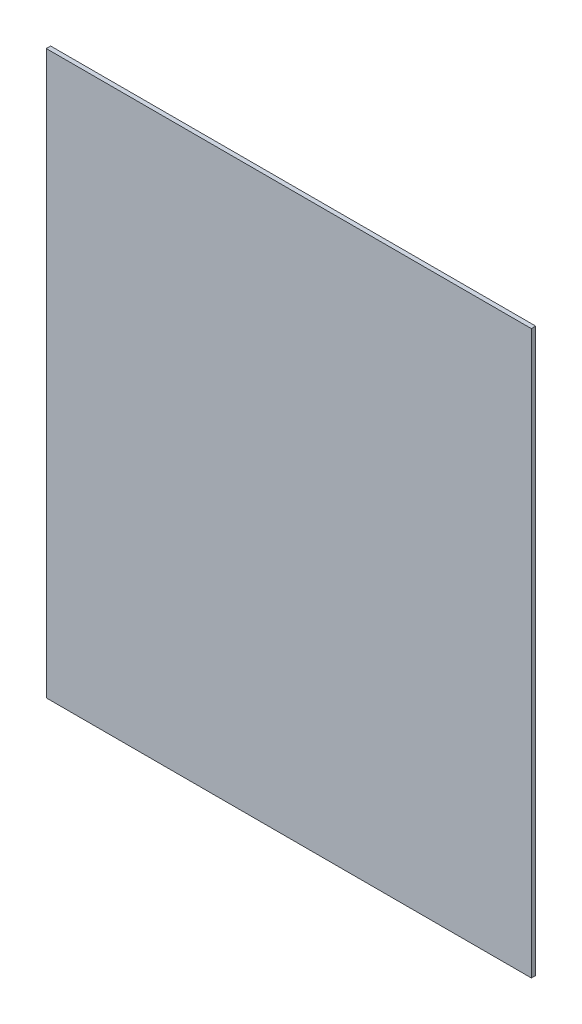
SolidWorks part; units mm, degrees
ref_plane "Plan de face" through (0, 0, 0) normal (0, 0, 1) x (1, 0, 0)
ref_plane "Plan de dessus" through (0, 0, 0) normal (0, 1, 0) x (1, 0, 0)
ref_plane "Plan de droite" through (0, 0, 0) normal (1, 0, 0) x (0, 0, -1)
sketch "Esquisse1" plane through (0, 0, 0) normal (0, 0, 1) x (1, 0, 0)
  line L1 (-361, -418.5) -> (361, -418.5)
  line L2 (-361, -418.5) -> (-361, 418.5)
  line L3 (-361, 418.5) -> (361, 418.5)
  line L4 (361, -418.5) -> (361, 418.5)
  line L5 (-361, -418.5) -> (361, 418.5) construction
  line L6 (-361, 418.5) -> (361, -418.5) construction
  point P0 (0, 0)
  dimension "D1" = 837
  dimension "D2" = 722
extrude "Boss.-Extru.1" add sketch "Esquisse1" along normal blind 6.5
